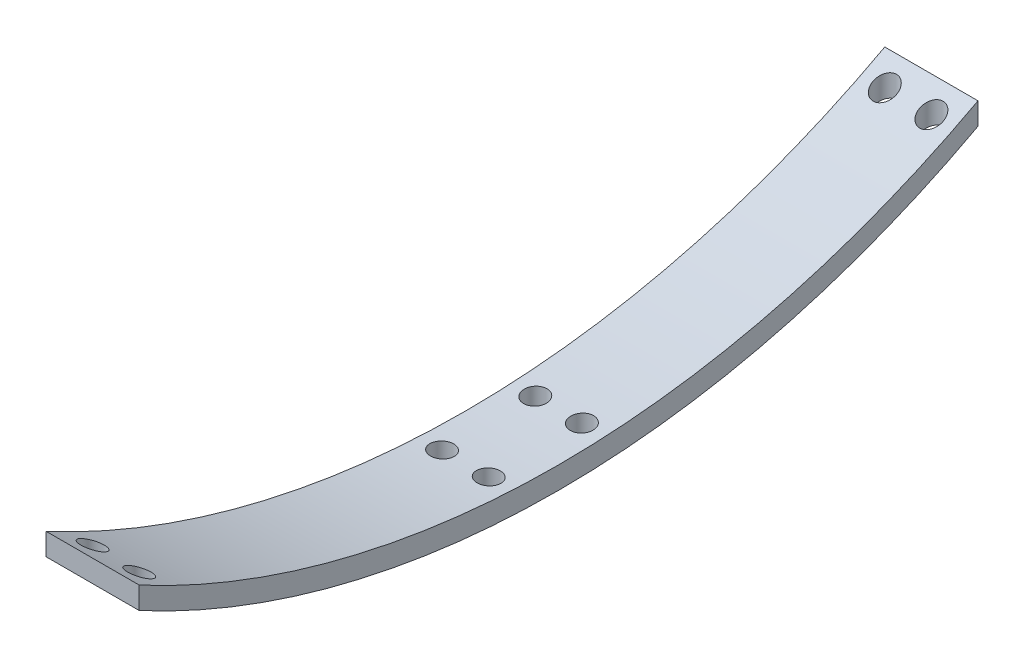
SolidWorks part; units mm, degrees
ref_plane "Front Plane" through (0, 0, 0) normal (0, 0, 1) x (1, 0, 0)
ref_plane "Top Plane" through (0, 0, 0) normal (0, 1, 0) x (1, 0, 0)
ref_plane "Right Plane" through (0, 0, 0) normal (1, 0, 0) x (0, 0, -1)
sketch "Sketch3" plane through (0, 0, 0) normal (1, 0, 0) x (0, 0, -1)
  line L0 (-8.3933, 1.9614) -> (-8.3933, -4.052)
  line L6 (-8.3933, -4.3886) -> (-8.3933, 1.9614)
  line L8 (232.9067, -4.3886) -> (232.9067, 1.9614)
  line L9 (232.9067, -4.052) -> (232.9067, 1.9614)
  arc A2 (-8.3933, 1.9614) -> (232.9067, 1.9614) centre (112.2567, 210.9333) ccw
  arc A3 (-8.3933, -4.052) -> (232.9067, -4.052) centre (112.2567, 204.9199) ccw
  dimension "D1" = 6.35
  dimension "D2" = 241.3
extrude "Boss-Extrude4" add sketch "Sketch3" along normal blind 304.8 contours L0 A3 L8 A2
ref_plane "Plane1" through (0, 1.9614, 0) normal (0, 1, 0) x (1, 0, 0)
sketch "Sketch4" plane through (0, 1.9614, 0) normal (0, 1, 0) x (1, 0, 0)
  line L0 (0, 232.9067) -> (28.689, 232.9067)
  line L1 (304.8, 232.9067) -> (0, 232.9067) construction
  line L2 (28.689, 232.9067) -> (28.689, 226.5567)
  line L3 (28.689, 226.5567) -> (28.689, -2.0433)
  line L4 (28.689, -2.0433) -> (28.689, -8.3933)
  line L5 (304.8, -8.3933) -> (0, -8.3933) construction
  line L7 (28.689, 226.5567) -> (54.089, 226.5567)
  line L8 (28.689, 226.5567) -> (28.689, -2.0433)
  line L9 (28.689, -2.0433) -> (54.089, -2.0433)
  line L10 (54.089, 226.5567) -> (54.089, -2.0433)
  dimension "D1" = 6.35
  dimension "D2" = 6.35
  dimension "D3" = 25.4
extrude "Cut-Extrude2" cut sketch "Sketch4" against normal blind 150 flip side to cut contours L8 L7 L10 L9
sketch "Sketch5" plane through (0, 1.9614, 0) normal (0, 1, 0) x (1, 0, 0)
  circle A0 centre (47.739, 220.2067) radius 3.175
  circle A1 centre (35.039, 220.2067) radius 3.175
  circle A2 centre (35.039, 4.3067) radius 3.175
  circle A3 centre (47.739, 4.3067) radius 3.175
extrude "Cut-Extrude3" cut sketch "Sketch5" against normal blind 150
sketch "Sketch6" plane through (0, 1.9614, 0) normal (0, 1, 0) x (1, 0, 0)
  circle A0 centre (35.039, 124.9567) radius 3.175
  circle A1 centre (47.739, 124.9567) radius 3.175
  circle A2 centre (35.039, 99.5567) radius 3.175
  circle A3 centre (47.739, 99.5567) radius 3.175
extrude "Cut-Extrude4" cut sketch "Sketch6" against normal blind 150
sketch "Sketch7" plane through (0, 1.9614, 0) normal (0, 1, 0) x (1, 0, 0)
  line L0 (54.089, 112.2567) -> (28.689, 112.2567)
  line L1 (54.089, 226.5567) -> (54.089, -2.0433) construction
  line L2 (28.689, 226.5567) -> (28.689, -2.0433) construction
  line L4 (28.689, 175.7567) -> (54.089, 175.7567)
  line L5 (28.689, 175.7567) -> (28.689, 48.7567)
  line L6 (28.689, 48.7567) -> (54.089, 48.7567)
  line L7 (54.089, 175.7567) -> (54.089, 48.7567)
  point P10 (54.089, 112.2567)
  point P11 (0, 0)
  dimension "D1" = 25.4
  dimension "D2" = 127
